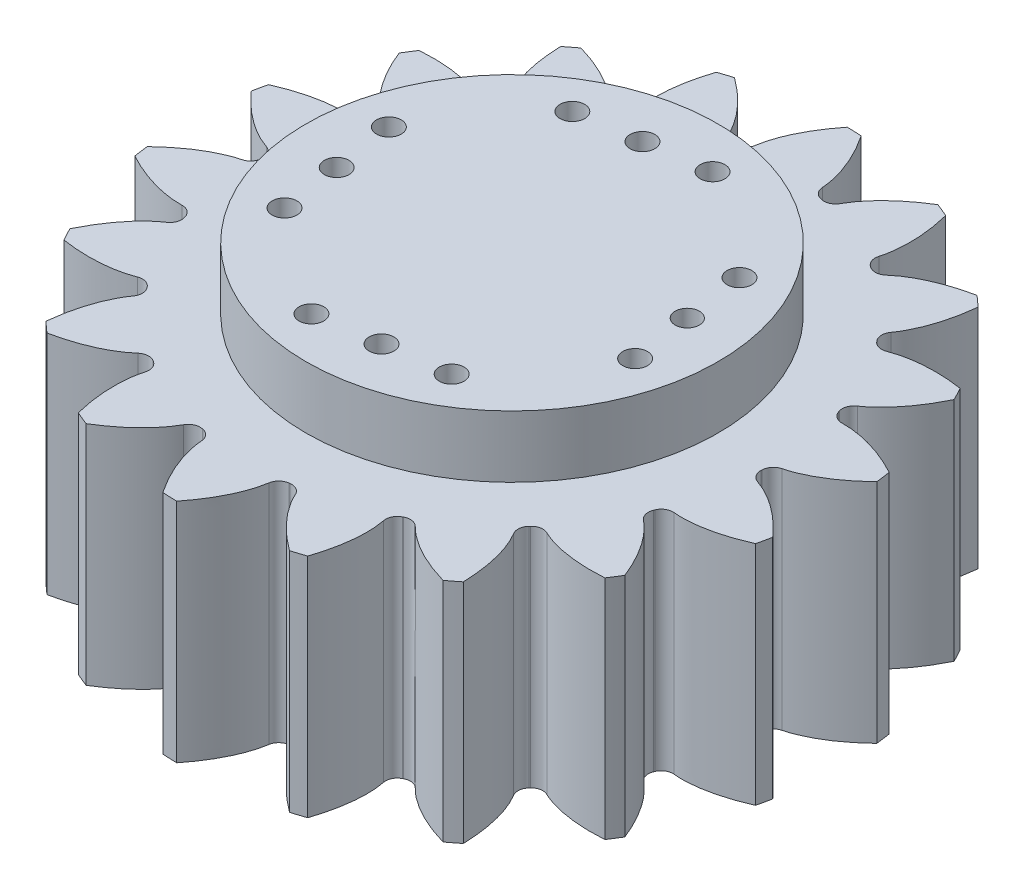
SolidWorks part; units mm, degrees
material "ABS"
ref_plane "Plan de face" through (0, 0, 0) normal (0, 0, 1) x (1, 0, 0)
ref_plane "Plan de dessus" through (0, 0, 0) normal (0, 1, 0) x (1, 0, 0)
ref_plane "Plan de droite" through (0, 0, 0) normal (1, 0, 0) x (0, 0, -1)
sketch "Esquisse1" plane through (0, 0, 0) normal (0, 1, 0) x (1, 0, 0)
  circle A0 centre (0, 0) radius 16
  circle A1 centre (0, 0) radius 12.625 construction
  circle A2 centre (0, 0) radius 14.5 construction
  circle A6 centre (0, 0) radius 14.6255 construction
  dimension "D1" = 29
  dimension "D7" = 29.2511
  dimension "D11" = 32
  dimension "D5" = 1.5
  dimension "D6" = 1.875
extrude "Boss.-Extru.1" add sketch "Esquisse1" along normal blind 11
sketch "Esquisse3" plane through (0, 0, 0) normal (0, 1, 0) x (1, 0, 0)
  spline S2 degree 4 poles (12.6859, 0) (12.6952, 0.0002) (12.7215, 0.0014) (12.7711, 0.006) (12.8517, 0.017) (12.9537, 0.036) (13.0846, 0.0664) (13.2374, 0.1094) (13.4034, 0.1643) (13.5818, 0.2322) (13.7575, 0.3069) (13.9305, 0.388) (14.1005, 0.4746) (14.3038, 0.5863) (14.5434, 0.7296) (14.8169, 0.9104) (15.1191, 1.1309) (15.4176, 1.3716) (15.7034, 1.6215) (15.9822, 1.8883) (16.2448, 2.1567) (16.5067, 2.4493) (16.7429, 2.7266) (16.9946, 3.0518) (17.1941, 3.3187) (17.4429, 3.6856) (17.5855, 3.9066) (17.7472, 4.1702) (17.8163, 4.2898) (17.859, 4.3634) knots 0 0 0 0 0 0.005377 0.015084 0.028532 0.04661 0.064855 0.092111 0.119476 0.146842 0.174209 0.201575 0.228941 0.256307 0.307035 0.361767 0.4165 0.471232 0.525964 0.580697 0.635429 0.690161 0.744894 0.799626 0.854358 0.909091 0.954545 1 1 1 1 1 construction
  spline S3 degree 4 poles (12.6859, 0) (12.6952, 0.0002) (12.7215, 0.0014) (12.7711, 0.006) (12.8517, 0.017) (12.9537, 0.036) (13.0846, 0.0664) (13.2374, 0.1094) (13.4034, 0.1643) (13.5818, 0.2322) (13.7575, 0.3069) (13.9305, 0.388) (14.1005, 0.4746) (14.3038, 0.5863) (14.5434, 0.7296) (14.8169, 0.9104) (15.1191, 1.1309) (15.4176, 1.3716) (15.7034, 1.6215) (15.9822, 1.8883) (16.2448, 2.1567) (16.5067, 2.4493) (16.7429, 2.7266) (16.9946, 3.0518) (17.1941, 3.3187) (17.3889, 3.606) (17.4821, 3.7475) (17.529, 3.8206) knots 0 0 0 0 0 0.005377 0.015084 0.028532 0.04661 0.064855 0.092111 0.119476 0.146842 0.174209 0.201575 0.228941 0.256307 0.307035 0.361767 0.4165 0.471232 0.525964 0.580697 0.635429 0.690161 0.744894 0.799626 0.854358 0.909091 0.909091 0.909091 0.909091 0.909091
sketch "Esquisse5" plane through (0, 0, 0) normal (0, 1, 0) x (1, 0, 0)
  line L0 (0, 0) -> (14.4888, -0.5693) construction
  line L1 (12.6859, 0) -> (12.625, 0)
  line L2 (12.6467, -0.9954) -> (12.5861, -0.9906)
  circle A0 centre (0, 0) radius 12.625 construction
  arc A1 (12.5861, -0.9906) -> (12.625, 0) centre (0, 0) ccw
  circle A2 centre (0, 0) radius 14.5 construction
  spline S1 degree 4 poles (2.8567, 999.8945) (10.3697, 17.4869) (11.2179, 0.3126) (12.0509, -0.0923) (12.8517, 0.017) (12.9537, 0.036) (13.0846, 0.0664) (13.2374, 0.1094) (13.4034, 0.1643) (13.5818, 0.2322) (13.7575, 0.3069) (13.9305, 0.388) (14.1005, 0.4746) (14.3038, 0.5863) (14.5434, 0.7296) (14.8169, 0.9104) (15.1191, 1.1309) (15.4176, 1.3716) (15.7034, 1.6215) (15.9822, 1.8883) (16.2448, 2.1567) (16.5067, 2.4493) (16.7429, 2.7266) (16.9946, 3.0518) (17.8359, 4.1774) (19.8937, 7.6762) (-0.4363, -23.3932) (557.0918, 845.7218) knots -0.4166 -0.4166 -0.4166 -0.4166 -0.4166 0.005377 0.015084 0.028532 0.04661 0.064855 0.092111 0.119476 0.146842 0.174209 0.201575 0.228941 0.256307 0.307035 0.361767 0.4165 0.471232 0.525964 0.580697 0.635429 0.690161 0.744894 0.799626 0.854358 1.613566 1.613566 1.613566 1.613566 1.613566 only from (12.6859, 0) to (17.529, 3.8206) construction
  spline S2 degree 4 poles (12.6859, 0) (12.6952, 0.0002) (12.7215, 0.0014) (12.7711, 0.006) (12.8517, 0.017) (12.9537, 0.036) (13.0846, 0.0664) (13.2374, 0.1094) (13.4034, 0.1643) (13.5818, 0.2322) (13.7575, 0.3069) (13.9305, 0.388) (14.1005, 0.4746) (14.3038, 0.5863) (14.5434, 0.7296) (14.8169, 0.9104) (15.1191, 1.1309) (15.4176, 1.3716) (15.7034, 1.6215) (15.9822, 1.8883) (16.2448, 2.1567) (16.5067, 2.4493) (16.7429, 2.7266) (16.9946, 3.0518) (17.1941, 3.3187) (17.3889, 3.606) (17.4821, 3.7475) (17.529, 3.8206) knots 0 0 0 0 0 0.005377 0.015084 0.028532 0.04661 0.064855 0.092111 0.119476 0.146842 0.174209 0.201575 0.228941 0.256307 0.307035 0.361767 0.4165 0.471232 0.525964 0.580697 0.635429 0.690161 0.744894 0.799626 0.854358 0.909091 0.909091 0.909091 0.909091 0.909091
  spline S3 degree 4 poles (12.6467, -0.9954) (12.6561, -0.9963) (12.6822, -0.9996) (12.7312, -1.0081) (12.8107, -1.0254) (12.9109, -1.0524) (13.0391, -1.0929) (13.188, -1.1478) (13.3492, -1.2155) (13.5217, -1.2972) (13.691, -1.3855) (13.8571, -1.4799) (14.0198, -1.5796) (14.2137, -1.7069) (14.4413, -1.8685) (14.6998, -2.0702) (14.9838, -2.3137) (15.2625, -2.5772) (15.5277, -2.8487) (15.7847, -3.1366) (16.0255, -3.4247) (16.2636, -3.7369) (16.4773, -4.0319) (16.7028, -4.3759) (16.8807, -4.6576) (17.0524, -4.9593) (17.1341, -5.1077) (17.1751, -5.1842) knots 0 0 0 0 0 0.005377 0.015084 0.028532 0.04661 0.064855 0.092111 0.119476 0.146842 0.174209 0.201575 0.228941 0.256307 0.307035 0.361767 0.4165 0.471232 0.525964 0.580697 0.635429 0.690161 0.744894 0.799626 0.854358 0.909091 0.909091 0.909091 0.909091 0.909091
  point P6 (14.4833, 0.6956)
  dimension "D1" = 5
extrude "Enlèv. mat.-Extru.1" cut sketch "Esquisse5" against normal through all and the other way through all
fillet "Congé1" radius 0.57 2 edges at (12.5861, 5.5, 0.9906) (12.625, 5.5, 0)
pattern_circular "Répétition circulaire1" count 18 over 360 about axis through (0, 11, 0) along (0, 1, 0) of "Enlèv. mat.-Extru.1", "Congé1"
sketch "Esquisse6" plane through (0, 11, 0) normal (0, 1, 0) x (1, 0, 0)
  line L0 (-8.5, 0) -> (8.5, 0) construction
  circle A0 centre (0, 0) radius 4
  circle A1 centre (-8.5, 0) radius 1.2
  circle A2 centre (8.5, 0) radius 1.2
  dimension "D1" = 8
  dimension "D2" = 17
  dimension "D3" = 2.4
extrude "Enlèv. mat.-Extru.2" cut sketch "Esquisse6" against normal through all
sketch "Sketch1" plane through (0, 11, 0) normal (0, 1, 0) x (1, 0, 0)
  circle A0 centre (0, 0) radius 10
  dimension "D1" = 20
extrude "Boss-Extrude1" add sketch "Sketch1" along normal blind 3
sketch "Sketch3" plane through (0, 14, 0) normal (0, 1, 0) x (1, 0, 0)
  circle A0 centre (6.9853, 4.0565) radius 0.6
  circle A1 centre (7.4206, 1.0883) radius 0.5875
  circle A2 centre (7.8559, -1.88) radius 0.6
  circle A3 centre (1.88, 7.8559) radius 0.6
  circle A4 centre (-1.0883, 7.4206) radius 0.6
  circle A5 centre (-4.0565, 6.9853) radius 0.6
  circle A6 centre (-7.8559, 1.88) radius 0.6
  circle A7 centre (-7.4206, -1.0883) radius 0.6
  circle A8 centre (-6.9853, -4.0565) radius 0.6
  circle A9 centre (-1.88, -7.8559) radius 0.6
  circle A10 centre (1.0883, -7.4206) radius 0.6
  circle A11 centre (4.0565, -6.9853) radius 0.6
extrude "Cut-Extrude2" cut sketch "Sketch3" against normal blind 3
equation "\"D1@Esquisse1\"=\"Module\" * \"Z1\"+2"
equation "\"Module\"= 1.5'module"
equation "\"Z1\"= 18'nb de dents"
equation "\"D5@Esquisse1\"=\"Module\""
equation "\"D6@Esquisse1\"=\"Module\"*1.25"
equation "\"a\"= 20'angle pression"
equation "\"D7@Esquisse1\"=\"D1@Esquisse1\"*cos( \"a\")+2"
equation "\"rayon\"= \"Module\" * 0.38'R fond de dent"
equation "\"D1@Esquisse5\"=360/\"Z1\"/4"
equation "\"D1@Répétition circulaire1\"=\"Z1\""
equation "\"D1@Congé1\"=\"rayon\""
